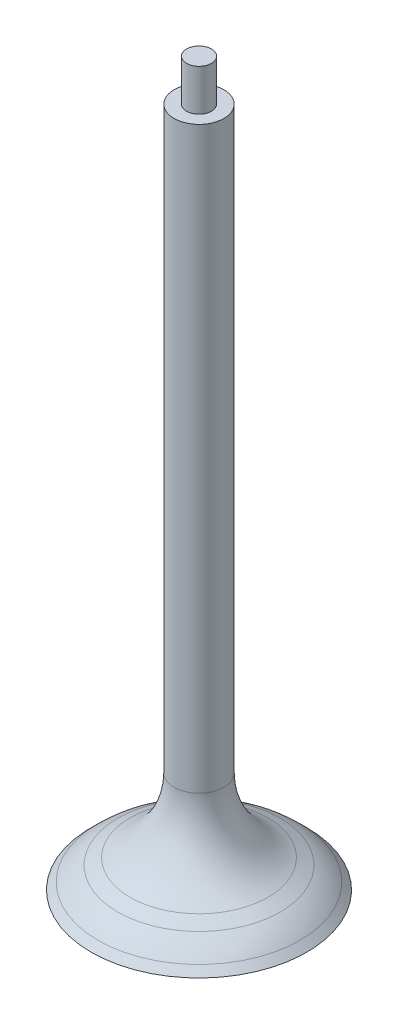
SolidWorks part; units mm, degrees
ref_plane "Front Plane" through (0, 0, 0) normal (0, 0, 1) x (1, 0, 0)
ref_plane "Top Plane" through (0, 0, 0) normal (0, 1, 0) x (1, 0, 0)
ref_plane "Right Plane" through (0, 0, 0) normal (1, 0, 0) x (0, 0, -1)
sketch "Sketch1" plane through (0, 0, 0) normal (0, 0, 1) x (1, 0, 0)
  line L9 (0, 0) -> (0, 87)
  line L10 (0, 87) -> (1.5, 87)
  line L11 (1.5, 87) -> (1.5, 82)
  line L12 (1.5, 82) -> (3, 82)
  line L13 (3, 82) -> (3, 6.2)
  line L14 (3, 6.2) -> (11.1146, 1.8854)
  line L16 (13, 0) -> (0, 0)
  line L17 (11.1146, 1.8854) -> (13, 0)
  dimension "D1" = 87
  dimension "D2" = 13
  dimension "D3" = 1.5
  dimension "D4" = 5
  dimension "D5" = 118
  dimension "D6" = 45
  dimension "D7" = 6.2
  dimension "D8" = 3
revolve "Revolve1" add sketch "Sketch1" angle 360 about L9
fillet "Fillet1" radius 10 1 edges at (0, 6.2, -3)
fillet "Fillet2" radius 10 1 edges at (0, 1.8854, -11.1146)
